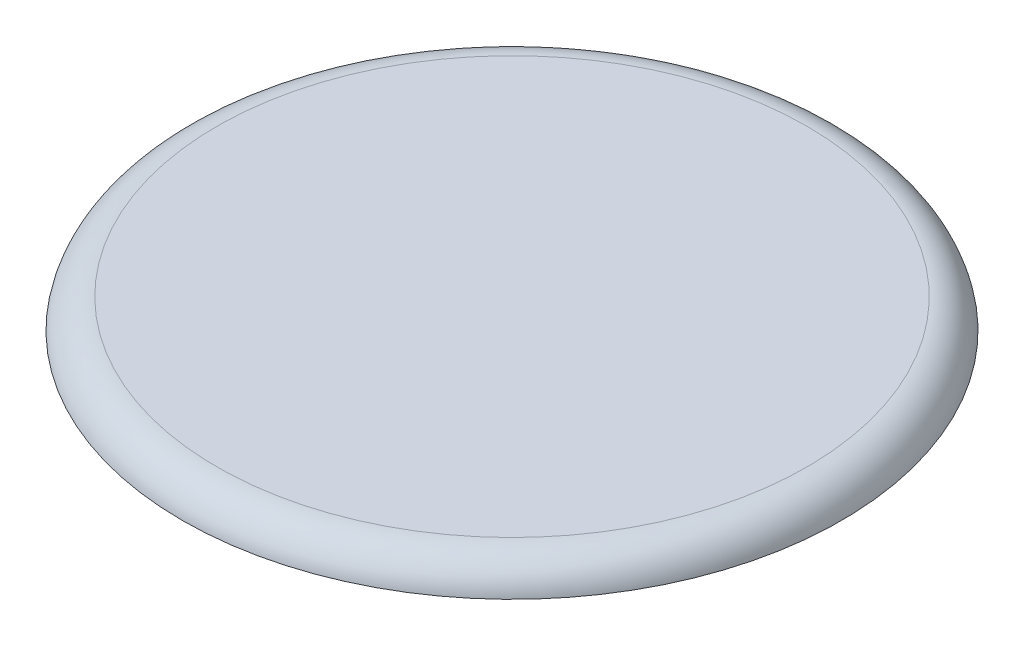
SolidWorks part; units mm, degrees
ref_plane "Front Plane" through (0, 0, 0) normal (0, 0, 1) x (1, 0, 0)
ref_plane "Top Plane" through (0, 0, 0) normal (0, 1, 0) x (1, 0, 0)
ref_plane "Right Plane" through (0, 0, 0) normal (1, 0, 0) x (0, 0, -1)
sketch "Sketch1" plane through (0, 0, 0) normal (0, 0, 1) x (1, 0, 0)
  line L0 (0, 0) -> (0, 5) construction
  line L1 (0, 5) -> (50.5839, 5)
  line L2 (47, 0) -> (47, 1.5)
  line L3 (56.5, 0) -> (0, 0)
  line L4 (47, 1.5) -> (0, 1.5)
  line L5 (0, 1.5) -> (0, 5)
  arc A0 (56.5, 0) -> (50.5839, 5) centre (50.5839, -1) ccw
  dimension "D2" = 6
  dimension "D1" = 5
  dimension "D3" = 113
  dimension "D4" = 1.5
  dimension "D5" = 94
revolve "Revolve1" add sketch "Sketch1" angle 360 about L0
sketch "Sketch2" plane through (0, 0, 0) normal (0, -1, 0) x (1, 0, 0)
  circle A0 centre (0, 51.91) radius 1.785
  circle A1 centre (51.91, 0) radius 1.785
  circle A2 centre (0, -51.91) radius 1.785
  circle A3 centre (-51.91, 0) radius 1.785
  point P12 (0, 0)
  dimension "D1" = 51.91
  dimension "D2" = 3.57
  dimension "D3" = 4
extrude "Cut-Extrude1" cut sketch "Sketch2" against normal blind 1.5
